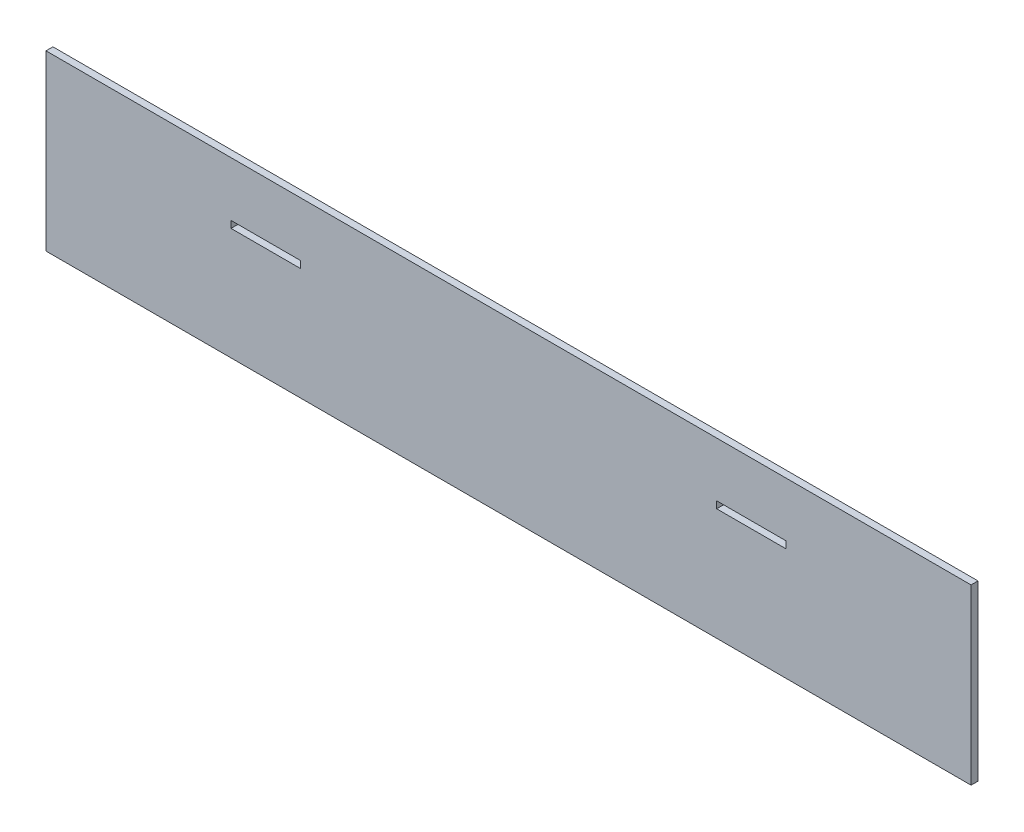
SolidWorks part; units mm, degrees
ref_plane "Alzado" through (0, 0, 0) normal (0, 0, 1) x (1, 0, 0)
ref_plane "Planta" through (0, 0, 0) normal (0, 1, 0) x (1, 0, 0)
ref_plane "Vista lateral" through (0, 0, 0) normal (1, 0, 0) x (0, 0, -1)
sketch "Croquis1" plane through (0, 0, 0) normal (0, 0, 1) x (1, 0, 0)
  line L0 (-200, 12.5) -> (200, 12.5) construction
  line L1 (-200, 37.5) -> (200, 37.5)
  line L2 (-200, 37.5) -> (-200, -37.5)
  line L3 (-200, -37.5) -> (200, -37.5)
  line L4 (200, 37.5) -> (200, -37.5)
  line L5 (-200, 37.5) -> (200, -37.5) construction
  line L6 (-200, -37.5) -> (200, 37.5) construction
  line L7 (0, -37.5) -> (0, 37.5) construction
  line L8 (-120, 14) -> (-90, 14)
  line L9 (-120, 14) -> (-120, 11)
  line L10 (-120, 11) -> (-90, 11)
  line L11 (-90, 14) -> (-90, 11)
  line L12 (-120, 14) -> (-90, 11) construction
  line L13 (-120, 11) -> (-90, 14) construction
  line L14 (120, 14) -> (120, 11)
  line L15 (120, 11) -> (90, 11)
  line L16 (90, 14) -> (90, 11)
  line L17 (120, 14) -> (90, 14)
  point P0 (0, 0)
  point P8 (-105, 12.5)
  dimension "D1" = 75
  dimension "D2" = 400
  dimension "D3" = 50
  dimension "D4" = 3
  dimension "D5" = 30
  dimension "D6" = 80
extrude "Saliente-Extruir1" add sketch "Croquis1" along normal blind 3
